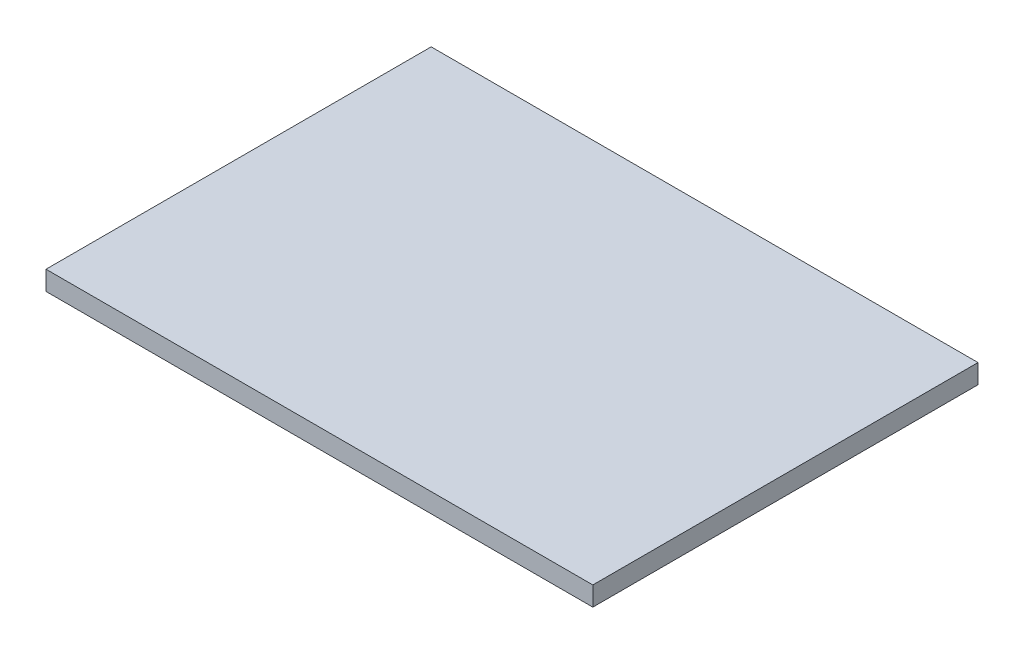
SolidWorks part; units mm, degrees
ref_plane "Front Plane" through (0, 0, 0) normal (0, 0, 1) x (1, 0, 0)
ref_plane "Top Plane" through (0, 0, 0) normal (0, 1, 0) x (1, 0, 0)
ref_plane "Right Plane" through (0, 0, 0) normal (1, 0, 0) x (0, 0, -1)
sketch "Sketch1" plane through (0, 0, 0) normal (0, 1, 0) x (1, 0, 0)
  line L1 (0, 0) -> (180.3, 0)
  line L2 (0, 0) -> (0, -127)
  line L3 (0, -127) -> (180.3, -127)
  line L4 (180.3, 0) -> (180.3, -127)
  dimension "D1" = 180.3
  dimension "D2" = 127
extrude "Boss-Extrude1" add sketch "Sketch1" along normal blind 6.35
